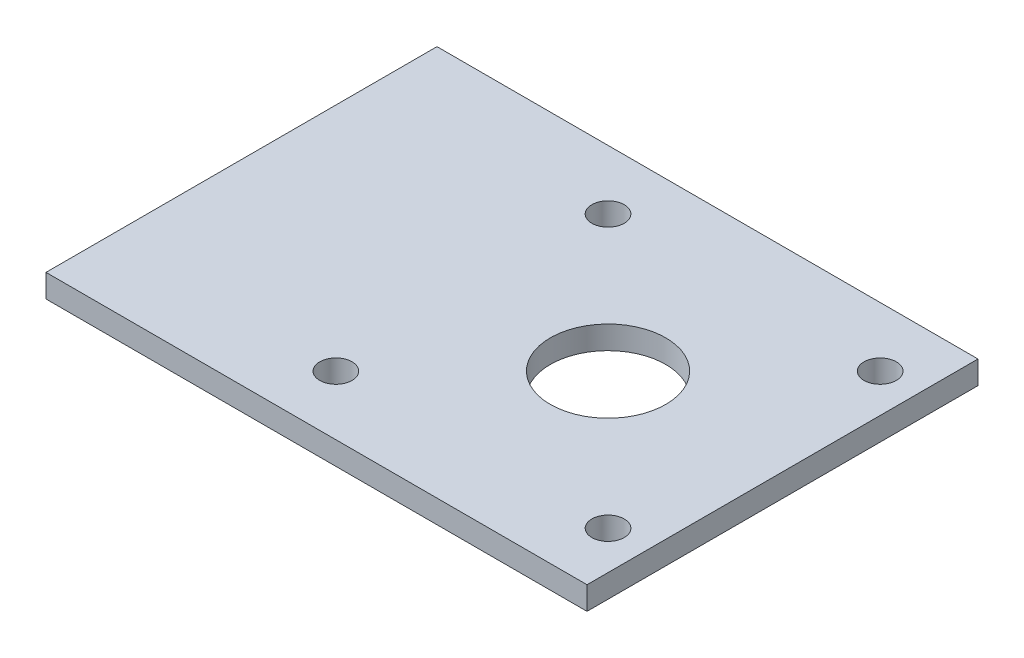
SolidWorks part; units mm, degrees
ref_plane "Front Plane" through (0, 0, 0) normal (0, 0, 1) x (1, 0, 0)
ref_plane "Top Plane" through (0, 0, 0) normal (0, 1, 0) x (1, 0, 0)
ref_plane "Right Plane" through (0, 0, 0) normal (1, 0, 0) x (0, 0, -1)
sketch "Sketch1" plane through (0, 0, 0) normal (0, 1, 0) x (1, 0, 0)
  line L1 (-47.625, 25.4) -> (47.625, 25.4)
  line L2 (-47.625, 25.4) -> (-47.625, -25.4)
  line L3 (-47.625, -25.4) -> (47.625, -25.4)
  line L4 (47.625, 25.4) -> (47.625, -25.4)
  line L5 (-47.625, 25.4) -> (47.625, -25.4) construction
  line L6 (-47.625, -25.4) -> (47.625, 25.4) construction
  point P0 (0, 0)
  dimension "D1" = 50.8
  dimension "D2" = 95.25
extrude "Boss-Extrude1" add sketch "Sketch1" along normal blind 3
sketch "Sketch2" plane through (0, 3, 0) normal (0, 1, 0) x (1, 0, 0)
  line L0 (-46.532, 0) -> (43.8345, 0) construction
  circle A0 centre (-17.68, 17.68) radius 2.1
  circle A1 centre (17.68, 17.68) radius 2.1
  circle A2 centre (17.68, -17.68) radius 2.1
  circle A3 centre (-17.68, -17.68) radius 2.1
  point P11 (0, 0)
  dimension "D1" = 4.2
  dimension "D2" = 4.2
  dimension "D3" = 17.68
  dimension "D4" = 17.68
  dimension "D5" = 17.68
  dimension "D6" = 17.68
extrude "Cut-Extrude1" cut sketch "Sketch2" against normal through all both and the other way through all contours A2 | A3 | A1 | A0
sketch "Sketch3" plane through (0, 3, 0) normal (0, 1, 0) x (1, 0, 0)
  line L0 (-20.6982, 25.4) -> (-20.6982, -25.4)
  line L1 (47.625, 25.4) -> (-47.625, 25.4) construction
  line L2 (-47.625, -25.4) -> (47.625, -25.4) construction
  line L3 (-20.6982, -25.4) -> (-47.625, -25.4)
  line L4 (-47.625, -25.4) -> (-47.625, 25.4)
  line L5 (-47.625, 25.4) -> (-20.6982, 25.4)
sketch "Sketch4" plane through (0, 3, 0) normal (0, 1, 0) x (1, 0, 0)
  circle A0 centre (0, 0) radius 7.5
  dimension "D1" = 15
extrude "Cut-Extrude3" cut sketch "Sketch4" against normal through all both and the other way through all
sketch "Sketch5" plane through (0, 3, 0) normal (0, 1, 0) x (1, 0, 0)
  line L0 (22.6694, 25.4) -> (22.6694, -25.4)
  line L1 (47.625, 25.4) -> (-47.625, 25.4) construction
  line L2 (-47.625, -25.4) -> (47.625, -25.4) construction
  line L3 (22.6694, -25.4) -> (47.625, -25.4)
  line L4 (47.625, -25.4) -> (47.625, 25.4)
  line L5 (47.625, 25.4) -> (22.6694, 25.4)
extrude "Cut-Extrude4" cut sketch "Sketch5" against normal through all both and the other way through all
